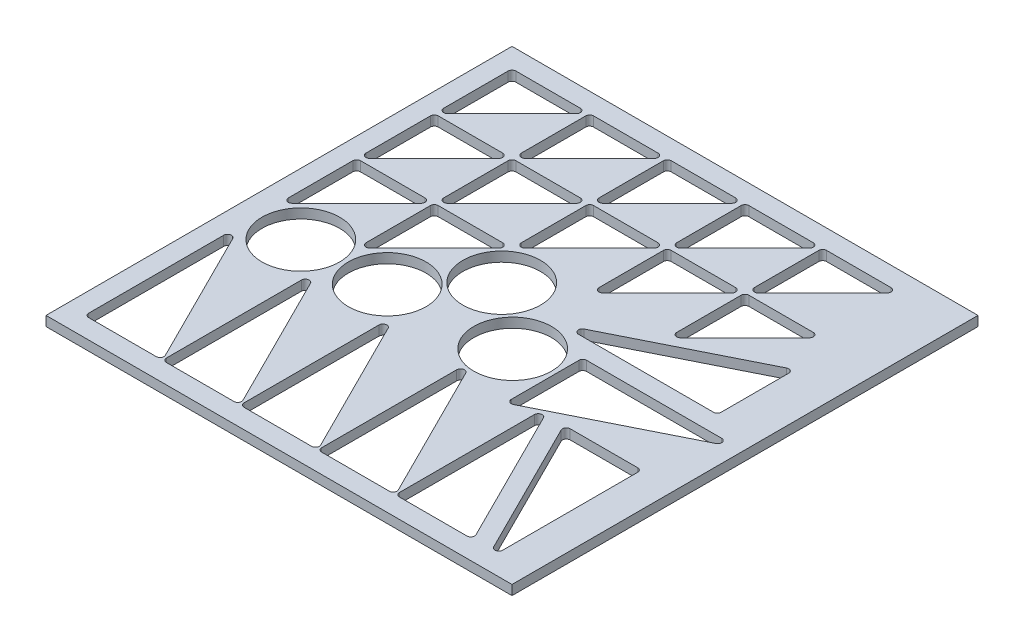
SolidWorks part; units mm, degrees
ref_plane "Front Plane" through (0, 0, 0) normal (0, 0, 1) x (1, 0, 0)
ref_plane "Top Plane" through (0, 0, 0) normal (0, 1, 0) x (1, 0, 0)
ref_plane "Right Plane" through (0, 0, 0) normal (1, 0, 0) x (0, 0, -1)
sketch "Sketch1" plane through (0, 0, 0) normal (0, 1, 0) x (1, 0, 0)
  line L6 (0, 0) -> (0, 304.8)
  line L7 (0, 0) -> (304.8, 0)
  line L8 (0, 304.8) -> (304.8, 304.8)
  line L9 (304.8, 0) -> (304.8, 304.8)
  dimension "D1" = 304.8
  dimension "D2" = 304.8
extrude "Boss-Extrude1" add sketch "Sketch1" along normal blind 6.35
sketch "Sketch2" plane through (0, 6.35, 0) normal (0, 1, 0) x (1, 0, 0)
  line L0 (12.7, 289.56) -> (12.7, 247.4321)
  line L1 (15.24, 292.1) -> (57.3679, 292.1)
  line L2 (17.0361, 245.6361) -> (59.1639, 287.7639)
  line L3 (304.8, 304.8) -> (0, 304.8) construction
  line L4 (0, 304.8) -> (0, 0) construction
  line L5 (67.8361, 245.6361) -> (109.9639, 287.7639)
  line L6 (66.04, 292.1) -> (108.1679, 292.1)
  line L7 (63.5, 289.56) -> (63.5, 247.4321)
  line L8 (118.6361, 245.6361) -> (160.7639, 287.7639)
  line L9 (116.84, 292.1) -> (158.9679, 292.1)
  line L10 (114.3, 289.56) -> (114.3, 247.4321)
  line L11 (169.4361, 245.6361) -> (211.5639, 287.7639)
  line L12 (167.64, 292.1) -> (209.7679, 292.1)
  line L13 (165.1, 289.56) -> (165.1, 247.4321)
  line L14 (220.2361, 245.6361) -> (262.3639, 287.7639)
  line L15 (218.44, 292.1) -> (260.5679, 292.1)
  line L16 (215.9, 289.56) -> (215.9, 247.4321)
  line L17 (67.8361, 194.8361) -> (109.9639, 236.9639)
  line L18 (66.04, 241.3) -> (108.1679, 241.3)
  line L19 (63.5, 238.76) -> (63.5, 196.6321)
  line L20 (118.6361, 194.8361) -> (160.7639, 236.9639)
  line L21 (116.84, 241.3) -> (158.9679, 241.3)
  line L22 (114.3, 238.76) -> (114.3, 196.6321)
  line L23 (169.4361, 194.8361) -> (211.5639, 236.9639)
  line L24 (167.64, 241.3) -> (209.7679, 241.3)
  line L25 (165.1, 238.76) -> (165.1, 196.6321)
  line L26 (220.2361, 194.8361) -> (262.3639, 236.9639)
  line L27 (218.44, 241.3) -> (260.5679, 241.3)
  line L28 (215.9, 238.76) -> (215.9, 196.6321)
  line L29 (17.0361, 194.8361) -> (59.1639, 236.9639)
  line L30 (15.24, 241.3) -> (57.3679, 241.3)
  line L31 (12.7, 238.76) -> (12.7, 196.6321)
  line L32 (17.0361, 144.0361) -> (59.1639, 186.1639)
  line L33 (15.24, 190.5) -> (57.3679, 190.5)
  line L34 (12.7, 187.96) -> (12.7, 145.8321)
  line L35 (67.8361, 144.0361) -> (109.9639, 186.1639)
  line L36 (66.04, 190.5) -> (108.1679, 190.5)
  line L37 (63.5, 187.96) -> (63.5, 145.8321)
  line L38 (12.7, 15.24) -> (12.7, 103.5404)
  line L39 (15.24, 12.7) -> (59.3902, 12.7)
  line L40 (0, 0) -> (304.8, 0) construction
  line L41 (17.5118, 104.6763) -> (61.662, 16.3759)
  line L42 (68.3118, 104.6763) -> (112.462, 16.3759)
  line L43 (66.04, 12.7) -> (110.1902, 12.7)
  line L44 (63.5, 15.24) -> (63.5, 103.5404)
  line L45 (119.1118, 104.6763) -> (163.262, 16.3759)
  line L46 (116.84, 12.7) -> (160.9902, 12.7)
  line L47 (114.3, 15.24) -> (114.3, 103.5404)
  line L48 (169.9118, 104.6763) -> (214.062, 16.3759)
  line L49 (167.64, 12.7) -> (211.7902, 12.7)
  line L50 (165.1, 15.24) -> (165.1, 103.5404)
  line L51 (220.7118, 104.6763) -> (264.862, 16.3759)
  line L52 (218.44, 12.7) -> (262.5902, 12.7)
  line L53 (215.9, 15.24) -> (215.9, 103.5404)
  line L54 (277.5522, 15.24) -> (233.402, 103.5404)
  line L55 (279.824, 107.2163) -> (235.6738, 107.2163)
  line L56 (282.364, 104.6763) -> (282.364, 16.3759)
  line L57 (291.6937, 146.5547) -> (203.3933, 102.4045)
  line L58 (199.7174, 148.8265) -> (199.7174, 104.6763)
  line L59 (202.2574, 151.3665) -> (290.5578, 151.3665)
  line L60 (183.6711, 168.254) -> (271.9715, 212.4042)
  line L61 (275.6474, 165.9822) -> (275.6474, 210.1324)
  line L62 (273.1074, 163.4422) -> (184.8071, 163.4422)
  arc A0 (59.1639, 287.7639) -> (57.3679, 292.1) centre (57.3679, 289.56) ccw
  arc A1 (12.7, 289.56) -> (15.24, 292.1) centre (15.24, 289.56) cw
  arc A2 (17.0361, 245.6361) -> (12.7, 247.4321) centre (15.24, 247.4321) cw
  arc A3 (67.8361, 245.6361) -> (63.5, 247.4321) centre (66.04, 247.4321) cw
  arc A4 (109.9639, 287.7639) -> (108.1679, 292.1) centre (108.1679, 289.56) ccw
  arc A5 (63.5, 289.56) -> (66.04, 292.1) centre (66.04, 289.56) cw
  arc A6 (118.6361, 245.6361) -> (114.3, 247.4321) centre (116.84, 247.4321) cw
  arc A7 (160.7639, 287.7639) -> (158.9679, 292.1) centre (158.9679, 289.56) ccw
  arc A8 (114.3, 289.56) -> (116.84, 292.1) centre (116.84, 289.56) cw
  arc A9 (169.4361, 245.6361) -> (165.1, 247.4321) centre (167.64, 247.4321) cw
  arc A10 (211.5639, 287.7639) -> (209.7679, 292.1) centre (209.7679, 289.56) ccw
  arc A11 (165.1, 289.56) -> (167.64, 292.1) centre (167.64, 289.56) cw
  arc A12 (220.2361, 245.6361) -> (215.9, 247.4321) centre (218.44, 247.4321) cw
  arc A13 (262.3639, 287.7639) -> (260.5679, 292.1) centre (260.5679, 289.56) ccw
  arc A14 (215.9, 289.56) -> (218.44, 292.1) centre (218.44, 289.56) cw
  arc A15 (67.8361, 194.8361) -> (63.5, 196.6321) centre (66.04, 196.6321) cw
  arc A16 (109.9639, 236.9639) -> (108.1679, 241.3) centre (108.1679, 238.76) ccw
  arc A17 (63.5, 238.76) -> (66.04, 241.3) centre (66.04, 238.76) cw
  arc A18 (118.6361, 194.8361) -> (114.3, 196.6321) centre (116.84, 196.6321) cw
  arc A19 (160.7639, 236.9639) -> (158.9679, 241.3) centre (158.9679, 238.76) ccw
  arc A20 (114.3, 238.76) -> (116.84, 241.3) centre (116.84, 238.76) cw
  arc A21 (169.4361, 194.8361) -> (165.1, 196.6321) centre (167.64, 196.6321) cw
  arc A22 (211.5639, 236.9639) -> (209.7679, 241.3) centre (209.7679, 238.76) ccw
  arc A23 (165.1, 238.76) -> (167.64, 241.3) centre (167.64, 238.76) cw
  arc A24 (220.2361, 194.8361) -> (215.9, 196.6321) centre (218.44, 196.6321) cw
  arc A25 (262.3639, 236.9639) -> (260.5679, 241.3) centre (260.5679, 238.76) ccw
  arc A26 (215.9, 238.76) -> (218.44, 241.3) centre (218.44, 238.76) cw
  arc A27 (17.0361, 194.8361) -> (12.7, 196.6321) centre (15.24, 196.6321) cw
  arc A28 (59.1639, 236.9639) -> (57.3679, 241.3) centre (57.3679, 238.76) ccw
  arc A29 (12.7, 238.76) -> (15.24, 241.3) centre (15.24, 238.76) cw
  arc A30 (59.1639, 186.1639) -> (57.3679, 190.5) centre (57.3679, 187.96) ccw
  arc A31 (12.7, 187.96) -> (15.24, 190.5) centre (15.24, 187.96) cw
  arc A32 (17.0361, 144.0361) -> (12.7, 145.8321) centre (15.24, 145.8321) cw
  arc A33 (109.9639, 186.1639) -> (108.1679, 190.5) centre (108.1679, 187.96) ccw
  arc A34 (63.5, 187.96) -> (66.04, 190.5) centre (66.04, 187.96) cw
  arc A35 (67.8361, 144.0361) -> (63.5, 145.8321) centre (66.04, 145.8321) cw
  arc A36 (59.3902, 12.7) -> (61.662, 16.3759) centre (59.3902, 15.24) ccw
  arc A37 (15.24, 12.7) -> (12.7, 15.24) centre (15.24, 15.24) cw
  arc A38 (17.5118, 104.6763) -> (12.7, 103.5404) centre (15.24, 103.5404) ccw
  arc A39 (68.3118, 104.6763) -> (63.5, 103.5404) centre (66.04, 103.5404) ccw
  arc A40 (110.1902, 12.7) -> (112.462, 16.3759) centre (110.1902, 15.24) ccw
  arc A41 (66.04, 12.7) -> (63.5, 15.24) centre (66.04, 15.24) cw
  arc A42 (119.1118, 104.6763) -> (114.3, 103.5404) centre (116.84, 103.5404) ccw
  arc A43 (160.9902, 12.7) -> (163.262, 16.3759) centre (160.9902, 15.24) ccw
  arc A44 (116.84, 12.7) -> (114.3, 15.24) centre (116.84, 15.24) cw
  arc A45 (169.9118, 104.6763) -> (165.1, 103.5404) centre (167.64, 103.5404) ccw
  arc A46 (211.7902, 12.7) -> (214.062, 16.3759) centre (211.7902, 15.24) ccw
  arc A47 (167.64, 12.7) -> (165.1, 15.24) centre (167.64, 15.24) cw
  arc A48 (220.7118, 104.6763) -> (215.9, 103.5404) centre (218.44, 103.5404) ccw
  arc A49 (262.5902, 12.7) -> (264.862, 16.3759) centre (262.5902, 15.24) ccw
  arc A50 (218.44, 12.7) -> (215.9, 15.24) centre (218.44, 15.24) cw
  arc A51 (277.5522, 15.24) -> (282.364, 16.3759) centre (279.824, 16.3759) ccw
  arc A52 (235.6738, 107.2163) -> (233.402, 103.5404) centre (235.6738, 104.6763) ccw
  arc A53 (279.824, 107.2163) -> (282.364, 104.6763) centre (279.824, 104.6763) cw
  circle A54 centre (40.3786, 126.2972) radius 25.4
  circle A58 centre (93.9645, 129.2119) radius 25.4
  circle A59 centre (130.5106, 167.5517) radius 25.4
  circle A60 centre (171.526, 133.6961) radius 25.4
  arc A61 (291.6937, 146.5547) -> (290.5578, 151.3665) centre (290.5578, 148.8265) ccw
  arc A62 (199.7174, 104.6763) -> (203.3933, 102.4045) centre (202.2574, 104.6763) ccw
  arc A63 (199.7174, 148.8265) -> (202.2574, 151.3665) centre (202.2574, 148.8265) cw
  arc A64 (183.6711, 168.254) -> (184.8071, 163.4422) centre (184.8071, 165.9822) ccw
  arc A65 (275.6474, 210.1324) -> (271.9715, 212.4042) centre (273.1074, 210.1324) ccw
  arc A66 (275.6474, 165.9822) -> (273.1074, 163.4422) centre (273.1074, 165.9822) cw
  point P7 (12.7, 268.4961)
  point P10 (63.5, 292.1)
  point P13 (12.7, 292.1)
  point P16 (12.7, 241.3)
  point P123 (63.5, 12.7)
  point P126 (12.7, 12.7)
  point P129 (12.7, 114.3)
  dimension "D5" = 2.54
  dimension "D13" = 2.54
  dimension "D1" = 50.8
  dimension "D2" = 50.8
  dimension "D3" = 12.7
  dimension "D4" = 12.7
  dimension "D9" = 12.7
  dimension "D10" = 101.6
  dimension "D11" = 12.7
  dimension "D12" = 50.8
  dimension "D6" = 5
  dimension "D7" = 2
  dimension "D8" = 2
  dimension "D14" = 5
extrude "Cut-Extrude2" cut sketch "Sketch2" against normal through all
